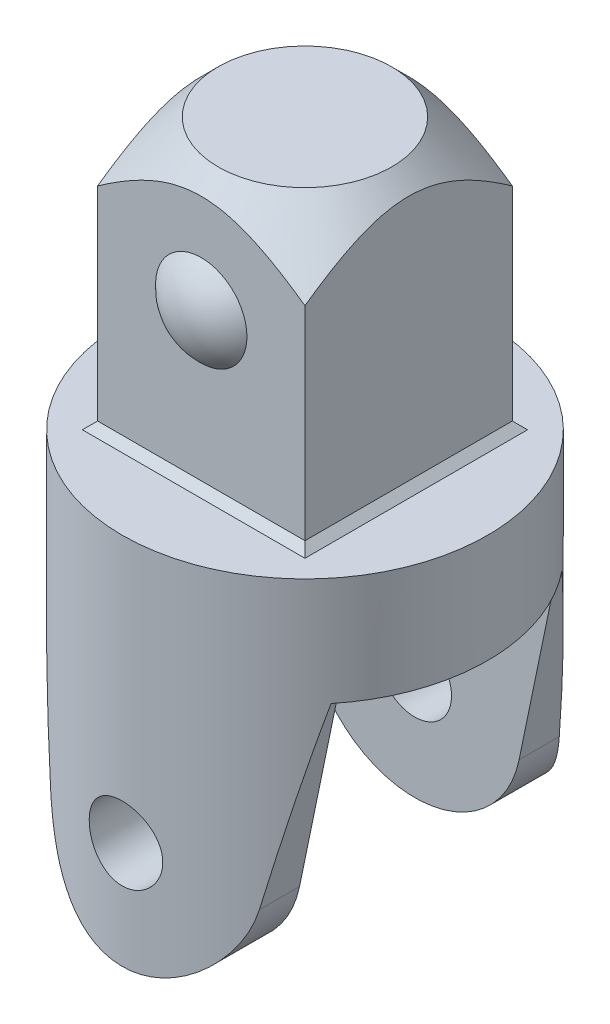
SolidWorks part; units mm, degrees
ref_plane "Front Plane" through (0, 0, 0) normal (0, 0, 1) x (1, 0, 0)
ref_plane "Top Plane" through (0, 0, 0) normal (0, 1, 0) x (1, 0, 0)
ref_plane "Right Plane" through (0, 0, 0) normal (1, 0, 0) x (0, 0, -1)
sketch "Sketch1" plane through (0, 0, 0) normal (0, 1, 0) x (1, 0, 0)
  circle A0 centre (0, 0) radius 12
  dimension "D1" = 24
extrude "Boss-Extrude1" add sketch "Sketch1" along normal blind 33.53
sketch "Sketch2" plane through (0, 33.53, 0) normal (0, 1, 0) x (1, 0, 0)
  line L0 (-6.5, 6.5) -> (-2.5, 6.5)
  line L1 (-6.5, 6.5) -> (6.5, 6.5) construction
  line L2 (-6.5, 6.5) -> (-6.5, -6.5) construction
  line L3 (-6.5, -6.5) -> (6.5, -6.5) construction
  line L4 (6.5, 6.5) -> (6.5, -6.5) construction
  line L5 (-6.5, 6.5) -> (6.5, -6.5) construction
  line L6 (-6.5, -6.5) -> (6.5, 6.5) construction
  line L7 (2.5, 6.5) -> (6.5, 6.5)
  line L8 (6.5, 6.5) -> (6.5, 2.5)
  line L9 (6.5, -2.5) -> (6.5, -6.5)
  line L10 (6.5, -6.5) -> (2.5, -6.5)
  line L11 (-2.5, -6.5) -> (-6.5, -6.5)
  line L12 (-6.5, -6.5) -> (-6.5, -2.5)
  line L13 (-6.5, 2.5) -> (-6.5, 6.5)
  arc A0 (-2.5, 6.5) -> (2.5, 6.5) centre (0, 2.4611) cw
  arc A1 (6.5, 2.5) -> (6.5, -2.5) centre (2.4611, 0) cw
  arc A2 (2.5, -6.5) -> (-2.5, -6.5) centre (0, -2.4611) cw
  arc A3 (-6.5, -2.5) -> (-6.5, 2.5) centre (-2.4611, 0) cw
  point P0 (0, 0)
  point P9 (0, 7.2111)
  point P28 (0, 0)
  dimension "D3" = 4.75
  dimension "D1" = 13
  dimension "D2" = 4
  dimension "D4" = 4
extrude "Cut-Extrude1" cut sketch "Sketch2" against normal blind 19.6
chamfer "Chamfer1" distance 0.4 angle 45 4 edges at (-6.5, 23.73, 6.5) (6.5, 23.73, 6.5) (-6.5, 23.73, -6.5) (6.5, 23.73, -6.5)
sketch "Sketch3" plane through (0, 33.53, 0) normal (0, 1, 0) x (1, 0, 0)
  circle A0 centre (0, 0) radius 9.375
  dimension "D1" = 18.75
extrude "Cut-Extrude2" cut sketch "Sketch3" against normal blind 3.4 draft 35
sketch "Sketch4" plane through (0, 0, 0) normal (0, -1, 0) x (1, 0, 0)
  line L1 (-12, 7.2111) -> (12, 7.2111)
  line L2 (-12, 7.2111) -> (-12, -7.2111)
  line L3 (-12, -7.2111) -> (12, -7.2111)
  line L4 (12, 7.2111) -> (12, -7.2111)
  arc A0 (2.5, 6.5) -> (-2.5, 6.5) centre (0, 2.4611) ccw construction
  arc A1 (-2.5, -6.5) -> (2.5, -6.5) centre (0, -2.4611) ccw construction
  circle A2 centre (0, 0) radius 12 construction
extrude "Cut-Extrude3" cut sketch "Sketch4" against normal blind 17.4
sketch "Sketch5" plane through (0, 0, 0) normal (0, 0, 1) x (1, 0, 0)
  line L0 (12, 17.4) -> (9.3, 17.4)
  line L1 (9.3, 17.4) -> (6.8548, 5.5817)
  line L2 (0, 0) -> (0, 33.53) construction
  line L3 (12, 33.53) -> (-12, 33.53) construction
  line L4 (-12, 17.4) -> (-9.3, 17.4)
  line L5 (-9.3, 17.4) -> (-6.8548, 5.5817)
  line L6 (-6.8548, 5.5817) -> (6.8548, 5.5817) construction
  line L7 (-12, 17.4) -> (-12, -3.1923)
  line L8 (-12, -3.1923) -> (12, -3.1923)
  line L9 (12, -3.1923) -> (12, 17.4)
  arc A0 (-6.8548, 5.5817) -> (6.8548, 5.5817) centre (0, 7) ccw
  circle A1 centre (0, 7) radius 2.415
  dimension "D1" = 7
  dimension "D3" = 4.83
  dimension "D2" = 2.7
extrude "Cut-Extrude4" cut sketch "Sketch5" against normal mid plane 67.4 contours A1 | A0 L5 L4 L7 L8 L9 L0 L1
sketch "Sketch6" plane through (0, 33.53, 0) normal (0, 1, 0) x (1, 0, 0)
  circle A0 centre (0, 0) radius 12
extrude "Cut-Extrude5" cut sketch "Sketch6" against normal blind 9
sketch "Sketch7" plane through (0, 24.53, 0) normal (0, 1, 0) x (1, 0, 0)
  circle A1 centre (0, 0) radius 12
  circle A2 centre (0, 0) radius 12
  dimension "D1" = 0
extrude "Boss-Extrude2" add sketch "Sketch7" against normal up to surface (7.13 mm away) up to face at (5.9936, 17.4, 0)
sketch "Sketch8" plane through (0, 24.53, 0) normal (0, 1, 0) x (1, 0, 0)
  line L1 (-6.81, 6.81) -> (6.81, 6.81)
  line L2 (-6.81, 6.81) -> (-6.81, -6.81)
  line L3 (-6.81, -6.81) -> (6.81, -6.81)
  line L4 (6.81, 6.81) -> (6.81, -6.81)
  line L5 (-6.81, 6.81) -> (6.81, -6.81) construction
  line L6 (-6.81, -6.81) -> (6.81, 6.81) construction
  point P0 (0, 0)
  dimension "D1" = 13.62
extrude "Boss-Extrude3" add sketch "Sketch8" along normal blind 17.8
ref_axis "Axis1" through (0, 44.4465, 0) along (0, -1, 0)
sketch "Sketch9" plane through (0, 0, 0) normal (0, 0, 1) x (1, 0, 0)
  line L0 (5.7, 42.33) -> (13.1113, 42.33)
  line L1 (-6.81, 42.33) -> (6.81, 42.33) construction
  line L2 (13.1113, 42.33) -> (13.1113, 34.9187)
  line L3 (13.1113, 34.9187) -> (5.7, 42.33)
  line L4 (0, 44.4465) -> (0, -2.1165) construction
  dimension "D1" = 45
  dimension "D2" = 5.7
revolve "Cut-Revolve1" cut sketch "Sketch9" angle 360 about axis through (0, 44.4465, 0) along (0, -1, 0)
chamfer "Chamfer2" distance 0.5 angle 45 4 edges at (0, 24.53, -6.81) (6.81, 24.53, 0) (-6.81, 24.53, 0) (0, 24.53, 6.81)
sketch "Sketch10" plane through (0, 0, 0) normal (1, 0, 0) x (0, 0, -1)
  line L0 (6.81, 34.73) -> (6.81, 31.73)
  line L1 (6.81, 38.3992) -> (6.81, 25.03) construction
  line L2 (6.81, 34.73) -> (8.16, 34.73) construction
  line L3 (5.7, 42.33) -> (-5.7, 42.33) construction
  line L4 (6.81, 34.73) -> (8.16, 34.73)
  arc A0 (8.16, 34.73) -> (6.81, 31.73) centre (4.1517, 34.73) cw
  dimension "D1" = 7.6
  dimension "D2" = 3
  dimension "D3" = 1.35
revolve "Revolve1" add sketch "Sketch10" angle 360 about L2
mirror "Mirror1" about plane through (0, 0, 0) normal (0, 0, 1) of "Revolve1"
